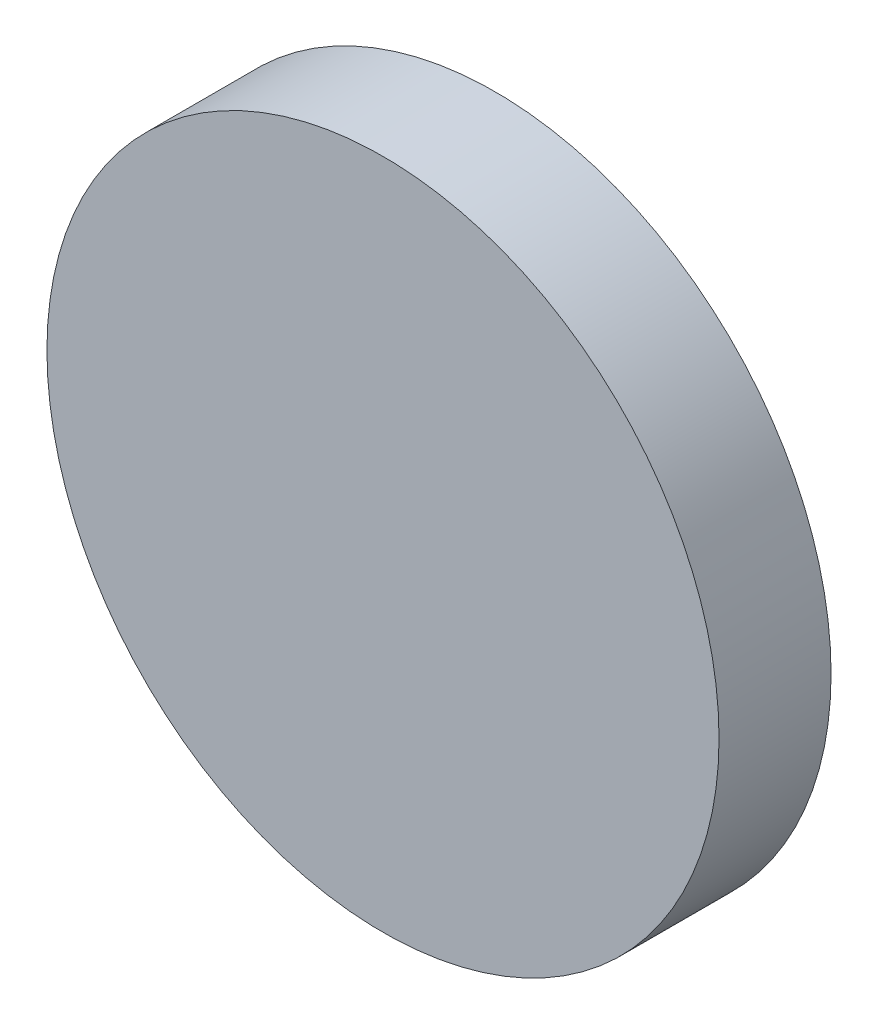
SolidWorks part; units mm, degrees
ref_plane "Front Plane" through (0, 0, 0) normal (0, 0, 1) x (1, 0, 0)
ref_plane "Top Plane" through (0, 0, 0) normal (0, 1, 0) x (1, 0, 0)
ref_plane "Right Plane" through (0, 0, 0) normal (1, 0, 0) x (0, 0, -1)
sketch "Sketch1" plane through (0, 0, 0) normal (0, 0, 1) x (1, 0, 0)
  circle A0 centre (0, 0) radius 3
  dimension "D1" = 6
extrude "Boss-Extrude1" add sketch "Sketch1" along normal blind 1
